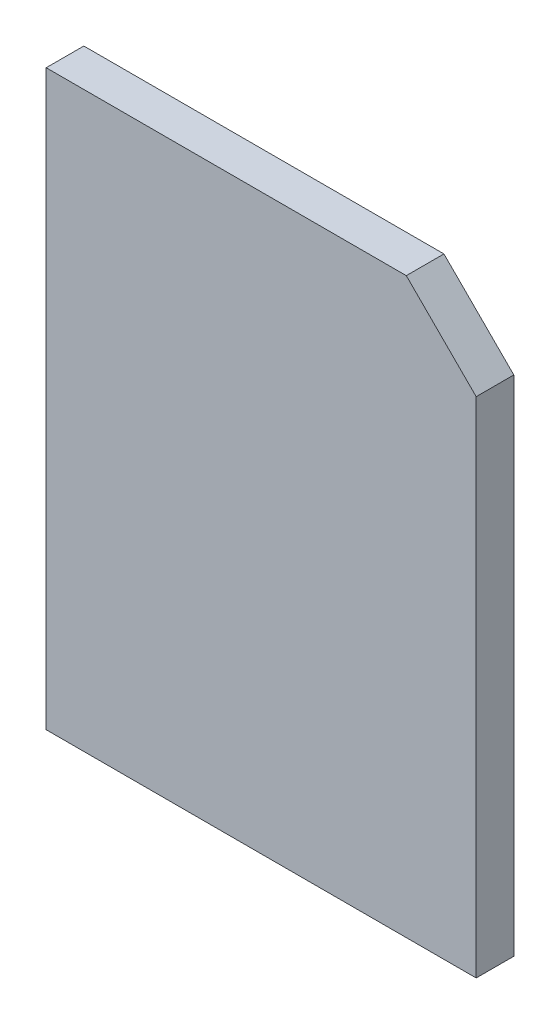
SolidWorks part; units mm, degrees
ref_plane "Front Plane" through (0, 0, 0) normal (0, 0, 1) x (1, 0, 0)
ref_plane "Top Plane" through (0, 0, 0) normal (0, 1, 0) x (1, 0, 0)
ref_plane "Right Plane" through (0, 0, 0) normal (1, 0, 0) x (0, 0, -1)
sketch "Sketch1" plane through (0, 0, 0) normal (0, 0, 1) x (1, 0, 0)
  line L1 (-12, -16) -> (12, -16)
  line L2 (-12, -16) -> (-12, 16)
  line L3 (-12, 16) -> (12, 16)
  line L4 (12, -16) -> (12, 16)
  line L5 (-12, -16) -> (12, 16) construction
  line L6 (-12, 16) -> (12, -16) construction
  point P0 (0, 0)
  dimension "D1" = 24
  dimension "D2" = 32
extrude "Boss-Extrude1" add sketch "Sketch1" along normal mid plane 2.1
sketch "Sketch2" plane through (0, 0, 1.05) normal (0, 0, 1) x (1, 0, 0)
  line L0 (12, 16) -> (8.1, 16)
  line L1 (12, 16) -> (-12, 16) construction
  line L2 (8.1, 16) -> (12, 12.1)
  line L3 (12, -16) -> (12, 16) construction
  line L4 (12, 12.1) -> (12, 16)
  dimension "D1" = 3.9
extrude "Cut-Extrude1" cut sketch "Sketch2" against normal through all
